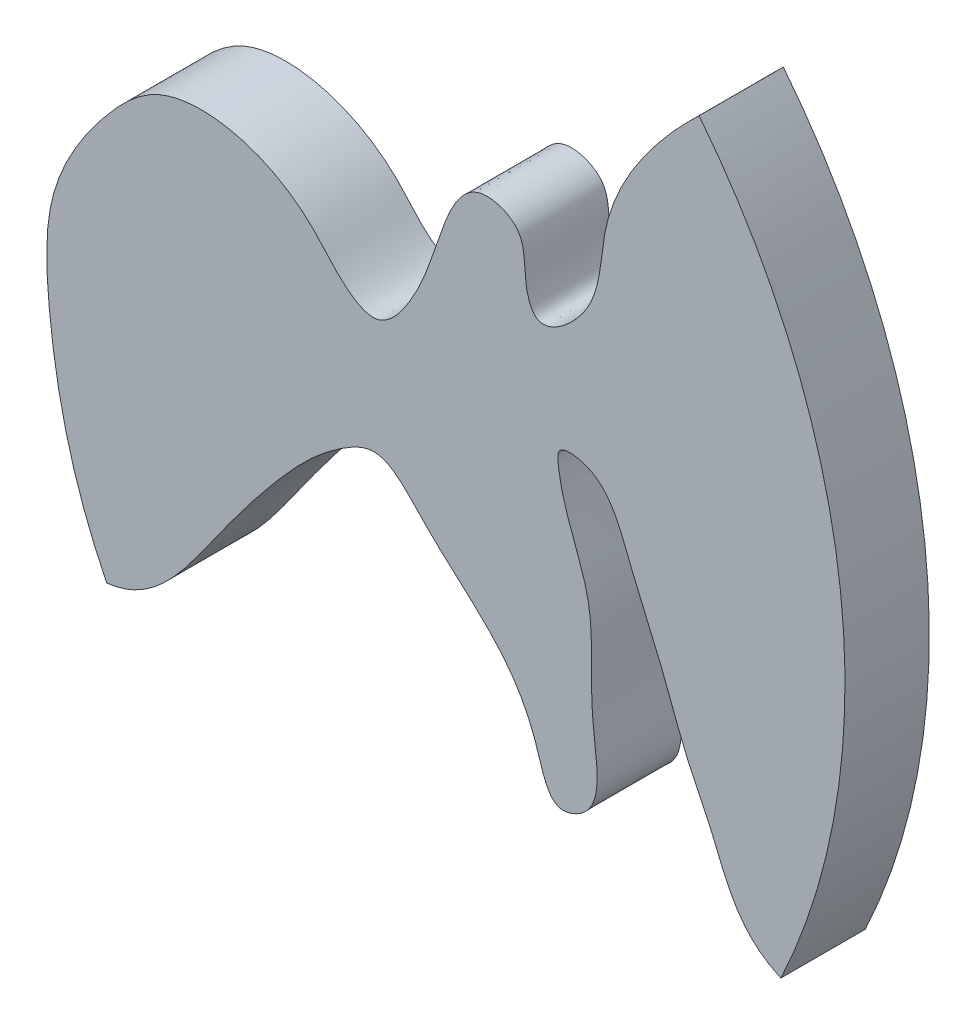
SolidWorks part; units mm, degrees
other "Camera1"
other "Camera2"
ref_plane "Front Plane" through (0, 0, 0) normal (0, 0, 1) x (1, 0, 0)
ref_plane "Top Plane" through (0, 0, 0) normal (0, 1, 0) x (1, 0, 0)
ref_plane "Right Plane" through (0, 0, 0) normal (1, 0, 0) x (0, 0, -1)
sketch "Sketch4" plane through (0, 0, 0) normal (0, 0, 1) x (1, 0, 0)
  line L0 (6.9108, 13.8216) -> (34.554, 13.8216) construction
  line L1 (6.9108, 13.8216) -> (34.554, 13.8216) construction
  line L3 (-21.3647, -9.2605) -> (54.8353, -9.2605)
  line L4 (-21.3647, -9.2605) -> (-21.3647, 16.1395)
  line L5 (-21.3647, 16.1395) -> (4.0353, 16.1395)
  line L6 (54.8353, -9.2605) -> (54.8353, 16.1395)
  line L7 (29.4353, 16.1395) -> (54.8353, 16.1395)
  circle A0 centre (16.7353, 16.1395) radius 12.7
  spline S0 degree 3 poles (5.2422, 10.736) (6.7181, 10.5583) (7.9181, 12.0335) (10.4689, 12.7659) (12.4429, 12.0981) (14.04, 10.9311) (16.2264, 10.6186) (17.4992, 12.5179) (18.6877, 14.1015) (19.6579, 15.1072) (20.7366, 15.6711) (21.5924, 14.6574) (22.7186, 13.7475) (23.5698, 12.7033) (23.8626, 11.2746) (24.9534, 11.6978) (24.5407, 13.3498) (24.8083, 15.1398) (24.095, 16.3012) (23.9989, 17.3316) (24.934, 17.3133) (25.3682, 16.0395) (25.9915, 14.7265) (26.4068, 13.4846) (27.1285, 12.1461) (27.37, 11.104) (28.2285, 10.736) knots 0 0 0 0 0.103449 0.139242 0.205578 0.258602 0.299466 0.363653 0.418235 0.461509 0.476758 0.506043 0.548409 0.597042 0.622241 0.632003 0.675048 0.726967 0.779124 0.786559 0.795901 0.835777 0.878716 0.917237 0.938498 1 1 1 1
  spline S1 degree 3 poles (6.3413, 8.8418) (7.3529, 8.8928) (8.4397, 9.7204) (10.0783, 10.5483) (11.6016, 10.3368) (13.0104, 9.4793) (14.603, 8.7601) (16.3539, 8.6272) (17.6381, 9.777) (19.2522, 10.6455) (19.4083, 12.2512) (20.6019, 13.0206) (21.5067, 11.9378) (22.2898, 10.7945) (23.033, 9.4552) (23.9852, 8.5414) (25.1785, 8.7836) (25.8581, 10.2364) (27.0204, 9.3268) (27.3242, 9.1277) knots 0 0 0 0 0.111112 0.158804 0.207675 0.281443 0.349359 0.412439 0.469148 0.544608 0.609897 0.643349 0.67797 0.748785 0.815451 0.856727 0.888905 0.942631 1 1 1 1
  spline S2 degree 3 poles (15.5303, 10.8283) (14.8939, 12.0951) (14.4389, 13.9813) (14.3435, 16.7343) (15.2691, 18.2447) (16.5062, 19.5074) (18.14, 19.4662) (19.332, 18.7362) (19.9024, 17.9655) (20.6817, 17.4716) (21.4483, 18.509) (21.7334, 19.5035) (22.2913, 20.9391) (23.5141, 20.4969) (23.333, 19.7355) (23.6787, 18.9513) (24.8928, 19.8566) (24.7041, 21.7986) (25.937, 23.3158) (26.6866, 24.0301) knots 0 0 0 0 0.163827 0.228295 0.314759 0.363733 0.427294 0.487534 0.520272 0.543413 0.580046 0.637018 0.68948 0.715614 0.7546 0.768001 0.802503 0.870836 1 1 1 1
  dimension "D1" = 25.4
  dimension "D2" = 25.4
  dimension "D3" = 76.2
extrude "Boss-Extrude1" add sketch "Sketch4" along normal blind 1.5875 contours S2 S0 A0
